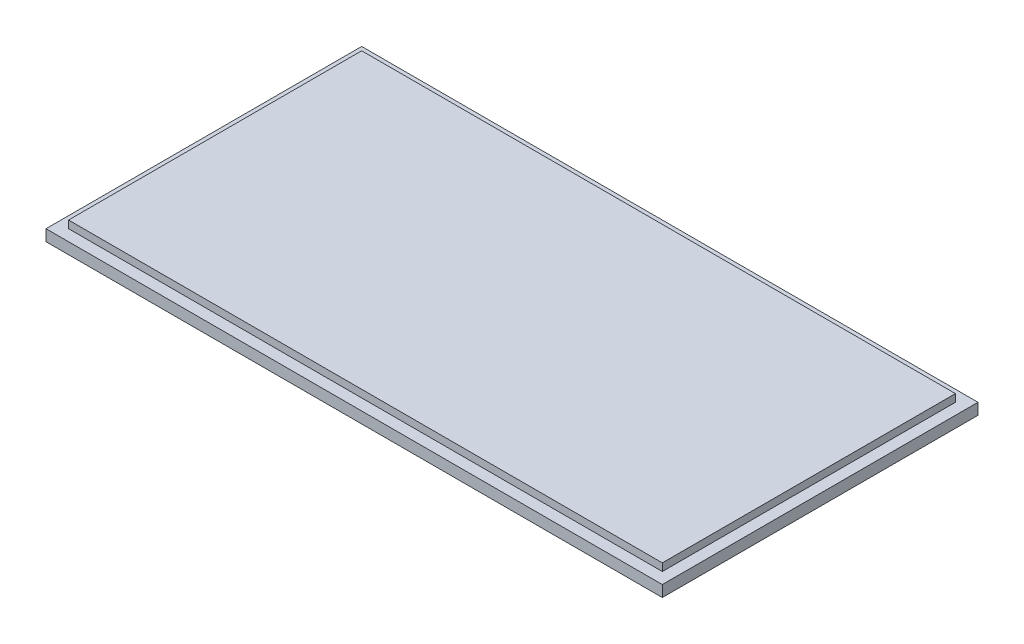
SolidWorks part; units mm, degrees
ref_plane "Front Plane" through (0, 0, 0) normal (0, 0, 1) x (1, 0, 0)
ref_plane "Top Plane" through (0, 0, 0) normal (0, 1, 0) x (1, 0, 0)
ref_plane "Right Plane" through (0, 0, 0) normal (1, 0, 0) x (0, 0, -1)
sketch "Sketch1" plane through (0, 0, 0) normal (0, 1, 0) x (1, 0, 0)
  line L1 (0, 0) -> (164, 0)
  line L2 (0, 0) -> (0, 84)
  line L3 (0, 84) -> (164, 84)
  line L4 (164, 0) -> (164, 84)
  dimension "D1" = 164
  dimension "D2" = 84
extrude "Boss-Extrude1" add sketch "Sketch1" along normal blind 3
sketch "Sketch2" plane through (0, 3, 0) normal (0, 1, 0) x (1, 0, 0)
  line L8 (3, 81) -> (3, 3)
  line L9 (3, 3) -> (161, 3)
  line L10 (161, 3) -> (161, 81)
  line L11 (161, 81) -> (3, 81)
  line L12 (3, 81) -> (3, 3)
  line L13 (3, 3) -> (161, 3)
  line L14 (161, 3) -> (161, 81)
  line L15 (161, 81) -> (3, 81)
  dimension "D1" = 3
extrude "Boss-Extrude2" add sketch "Sketch2" along normal blind 2
